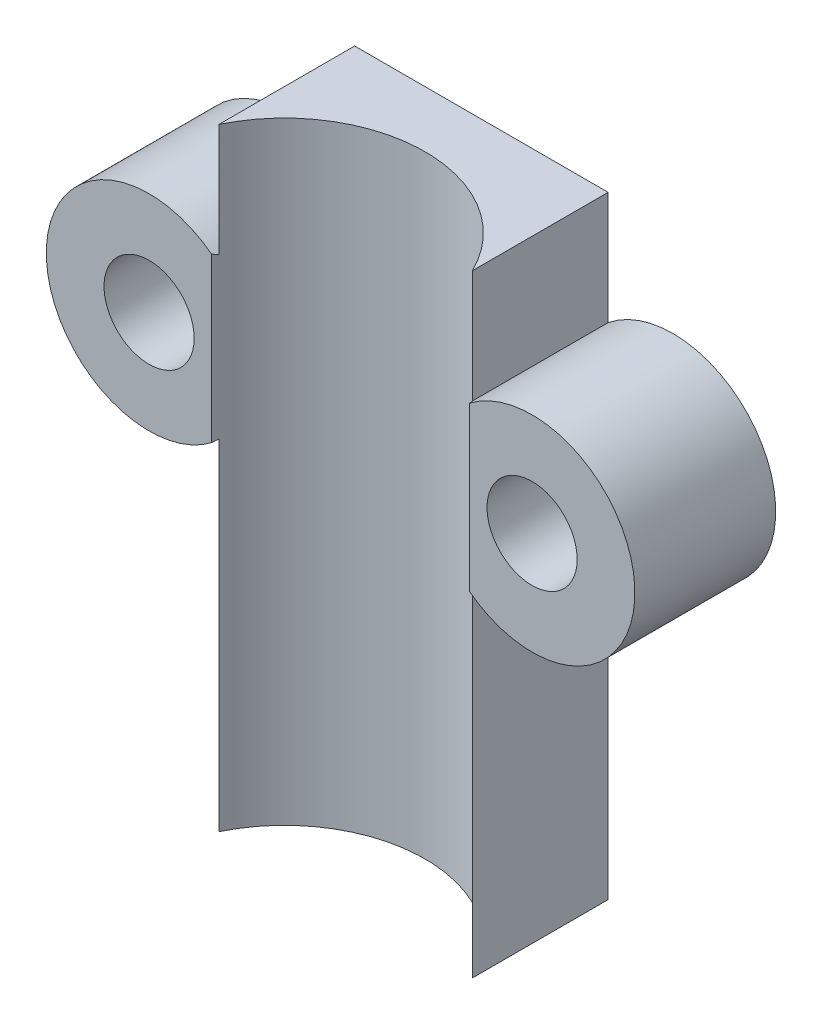
SolidWorks part; units mm, degrees
ref_plane "Front Plane" through (0, 0, 0) normal (0, 0, 1) x (1, 0, 0)
ref_plane "Top Plane" through (0, 0, 0) normal (0, 1, 0) x (1, 0, 0)
ref_plane "Right Plane" through (0, 0, 0) normal (1, 0, 0) x (0, 0, -1)
sketch "Sketch1" plane through (0, 0, 0) normal (0, 0, 1) x (1, 0, 0)
  line L0 (-156.4984, -8.568) -> (-142.8984, -8.568) construction
  line L5 (-154.1984, -11.4021) -> (-154.1984, -23.478)
  line L6 (-154.1984, -1.728) -> (-145.1984, -1.728)
  line L7 (-154.1984, -1.728) -> (-154.1984, -5.7338)
  line L8 (-154.1984, -23.478) -> (-145.1984, -23.478)
  line L9 (-145.1984, -1.728) -> (-145.1984, -5.7338)
  line L10 (-145.1984, -11.4021) -> (-145.1984, -23.478)
  arc A0 (-154.1984, -5.7338) -> (-154.1984, -11.4021) centre (-156.4984, -8.568) ccw
  arc A1 (-145.1984, -5.7338) -> (-145.1984, -11.4021) centre (-142.8984, -8.568) cw
  circle A2 centre (-156.4984, -8.568) radius 1.6
  circle A3 centre (-142.8984, -8.568) radius 1.6
  dimension "D5" = 3.65
  dimension "D6" = 3.2
  dimension "D1" = 13.6
  dimension "D2" = 9
  dimension "D3" = 2.3
  dimension "D4" = 6.84
  dimension "D7" = 21.75
extrude "Boss-Extrude1" add sketch "Sketch1" along normal blind 5
sketch "Sketch2" plane through (0, -1.728, 0) normal (0, 1, 0) x (1, 0, 0)
  line L0 (-149.6984, 0) -> (-149.6984, -5) construction
  line L1 (-145.1984, 0) -> (-154.1984, 0) construction
  line L2 (-145.1984, -5) -> (-154.1984, -5) construction
  circle A0 centre (-149.6984, -7) radius 5
  dimension "D1" = 10
  dimension "D2" = 7
extrude "Cut-Extrude1" cut sketch "Sketch2" against normal through all
